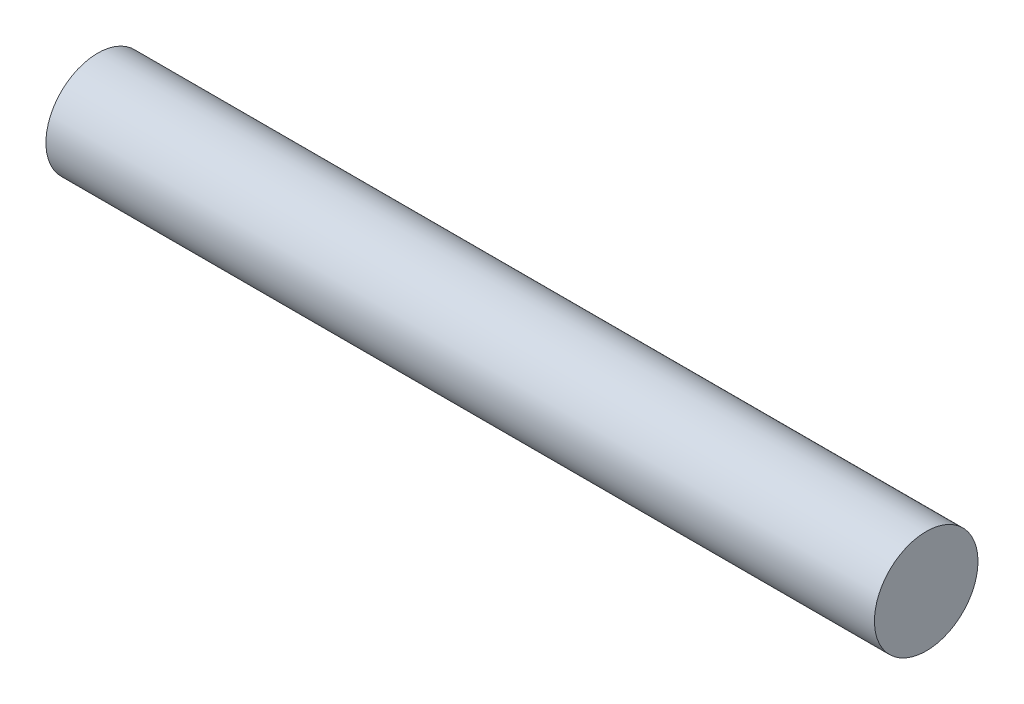
SolidWorks part; units mm, degrees
ref_plane "Plan de face" through (0, 0, 0) normal (0, 0, 1) x (1, 0, 0)
ref_plane "Plan de dessus" through (0, 0, 0) normal (0, 1, 0) x (1, 0, 0)
ref_plane "Plan de droite" through (0, 0, 0) normal (1, 0, 0) x (0, 0, -1)
sketch "Esquisse1" plane through (0, 0, 0) normal (1, 0, 0) x (0, 0, -1)
  circle A0 centre (0, 0) radius 1
  dimension "D1" = 2
extrude "Boss.-Extru.1" add sketch "Esquisse1" along normal blind 16
ref_plane "Plan1" through (8, 0, 0) normal (1, 0, 0) x (0, 0, -1)
